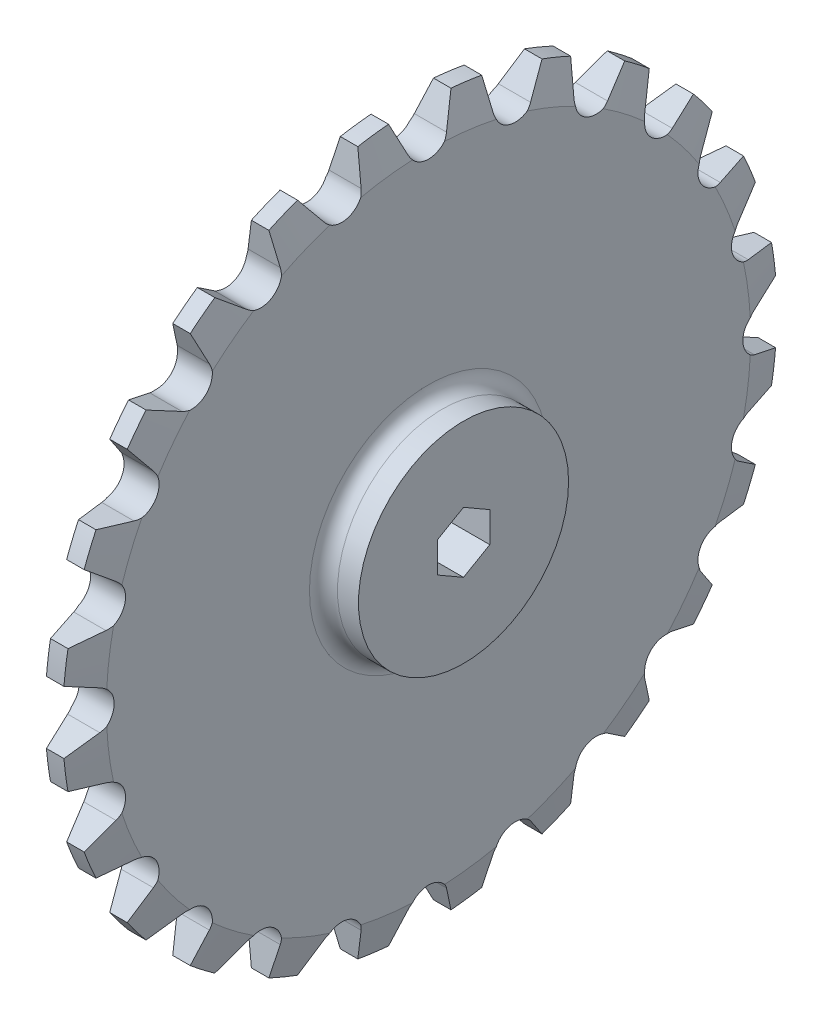
SolidWorks part; units mm, degrees
ref_plane "Front Plane" through (0, 0, 0) normal (0, 0, 1) x (1, 0, 0)
ref_plane "Top Plane" through (0, 0, 0) normal (0, 1, 0) x (1, 0, 0)
ref_plane "Right Plane" through (0, 0, 0) normal (1, 0, 0) x (0, 0, -1)
sketch "Sketch1" plane through (0, 0, 0) normal (0, 0, 1) x (1, 0, 0)
  line L0 (-6.35, 58.42) -> (-4.7625, 64.77)
  line L1 (0, 0) -> (-6.35, 0)
  line L2 (0, 0) -> (0, 58.42)
  line L3 (0, 58.42) -> (-6.35, 58.42)
  line L4 (-6.35, 0) -> (-6.35, 58.42)
  line L5 (-4.7625, 64.77) -> (-1.5875, 64.77)
  line L6 (-1.5875, 64.77) -> (0, 58.42)
  line L8 (0, 0) -> (6.35, 0)
  line L9 (0, 0) -> (0, 19.05)
  line L10 (0, 19.05) -> (6.35, 19.05)
  line L11 (6.35, 0) -> (6.35, 19.05)
  line L12 (-6.35, 0) -> (-19.05, 0)
  line L13 (-6.35, 0) -> (-6.35, 19.05)
  line L14 (-6.35, 19.05) -> (-19.05, 19.05)
  line L15 (-19.05, 0) -> (-19.05, 19.05)
  point P7 (-3.175, 64.77)
  point P8 (-3.175, 58.42)
  dimension "D1" = 3.175
  dimension "D2" = 6.35
  dimension "D3" = 58.42
  dimension "D4" = 6.35
  dimension "D5" = 12.7
  dimension "D6" = 6.35
  dimension "D7" = 19.05
revolve "Revolve1" add sketch "Sketch1" angle 360 about L1
sketch "Sketch2" plane through (0, 0, 0) normal (1, 0, 0) x (0, 0, -1)
  line L16 (52.6643, -30.4058) -> (58.7394, -15.7392)
  line L17 (0, 60.8115) -> (-15.7392, 58.7394)
  line L18 (-15.7392, 58.7394) -> (-30.4058, 52.6643)
  line L19 (-30.4058, 52.6643) -> (-43.0003, 43.0003)
  line L20 (-43.0003, 43.0003) -> (-52.6643, 30.4058)
  line L21 (-52.6643, 30.4058) -> (-58.7394, 15.7392)
  line L22 (-58.7394, 15.7392) -> (-60.8115, 0)
  line L23 (-60.8115, 0) -> (-58.7394, -15.7392)
  line L24 (-58.7394, -15.7392) -> (-52.6643, -30.4058)
  line L25 (-52.6643, -30.4058) -> (-43.0003, -43.0003)
  line L26 (-43.0003, -43.0003) -> (-30.4058, -52.6643)
  line L27 (-30.4058, -52.6643) -> (-15.7392, -58.7394)
  line L28 (-15.7392, -58.7394) -> (0, -60.8115)
  line L29 (0, -60.8115) -> (15.7392, -58.7394)
  line L30 (15.7392, -58.7394) -> (30.4058, -52.6643)
  line L31 (30.4058, -52.6643) -> (43.0003, -43.0003)
  line L32 (43.0003, -43.0003) -> (52.6643, -30.4058)
  line L33 (58.7394, -15.7392) -> (60.8115, 0)
  line L34 (60.8115, 0) -> (58.7394, 15.7392)
  line L35 (58.7394, 15.7392) -> (52.6643, 30.4058)
  line L36 (52.6643, 30.4058) -> (43.0003, 43.0003)
  line L37 (43.0003, 43.0003) -> (30.4058, 52.6643)
  line L38 (30.4058, 52.6643) -> (15.7392, 58.7394)
  line L39 (15.7392, 58.7394) -> (0, 60.8115)
  line L40 (-3.52, 59.3535) -> (-10.0164, 75.0373)
  line L41 (0, 0) -> (0, 60.8115) construction
  line L42 (3.52, 59.3535) -> (10.0164, 75.0373)
  line L43 (-10.0164, 75.0373) -> (10.0164, 75.0373)
  circle A0 centre (0, 0) radius 60.2913 construction
  circle A1 centre (0, 60.8115) radius 3.81
  dimension "D2" = 7.62
  dimension "D1" = 15.875
  dimension "D3" = 22.5
extrude "Cut-Extrude1" cut sketch "Sketch2" against normal through all both contours A1 L39 L42 L43 L40 L17 | L39 A1 L17 | L17 A1 L39 | A1 L42 L39 | A1 L17 L40
pattern_circular "CirPattern1" count 24 over 360 about axis through (0, 0, 0) along (1, 0, 0) of "Cut-Extrude1"
sketch "Sketch3" plane through (-19.05, 0, 0) normal (-1, 0, 0) x (0, 0, 1)
  line L1 (0, 5.4993) -> (-4.7625, 2.7496)
  line L2 (-4.7625, 2.7496) -> (-4.7625, -2.7496)
  line L3 (-4.7625, -2.7496) -> (0, -5.4993)
  line L4 (0, -5.4993) -> (4.7625, -2.7496)
  line L5 (4.7625, -2.7496) -> (4.7625, 2.7496)
  line L6 (4.7625, 2.7496) -> (0, 5.4993)
  circle A0 centre (0, 0) radius 4.7625 construction
  dimension "D1" = 9.525
extrude "Cut-Extrude2" cut sketch "Sketch3" against normal through all both
fillet "Fillet1" radius 2.54 2 edges at (0, 0, -19.05) (-6.35, 0, -19.05)
